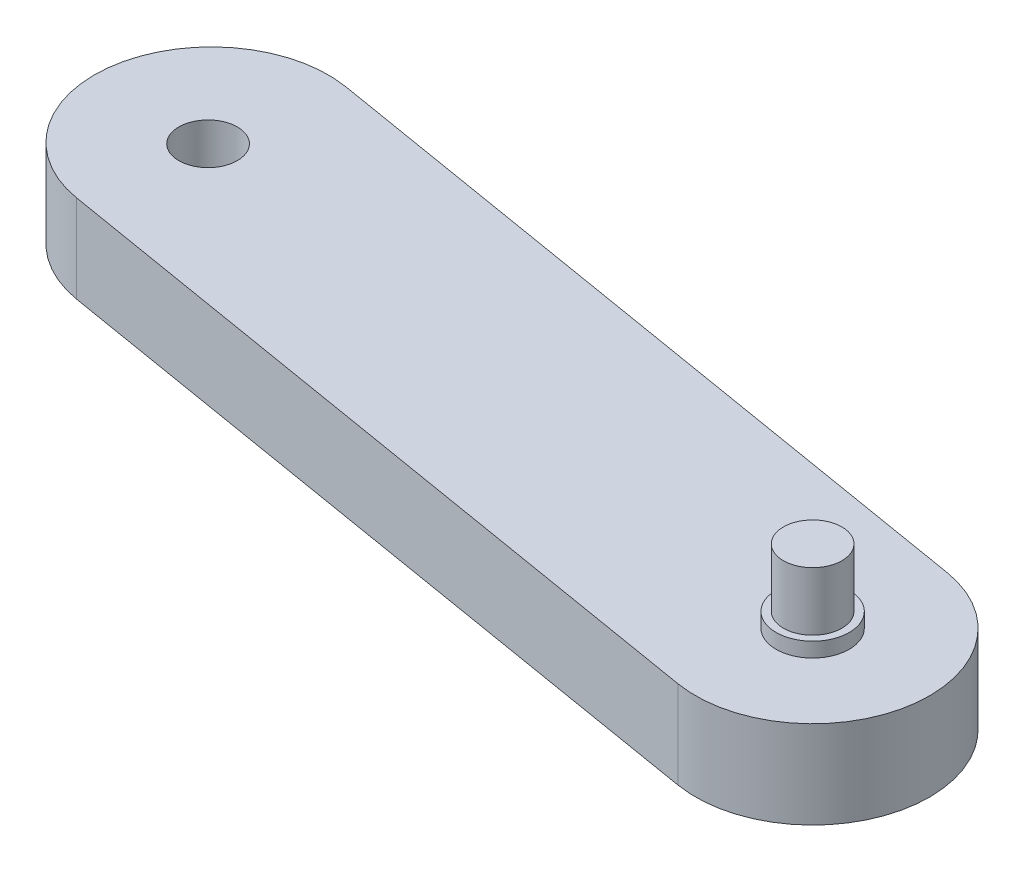
SolidWorks part; units mm, degrees
ref_plane "Piano frontale" through (0, 0, 0) normal (0, 0, 1) x (1, 0, 0)
ref_plane "Piano superiore" through (0, 0, 0) normal (0, 1, 0) x (1, 0, 0)
ref_plane "Piano destro" through (0, 0, 0) normal (1, 0, 0) x (0, 0, -1)
sketch "Sketch1" plane through (0, 0, 0) normal (0, 0, 1) x (1, 0, 0)
  line L0 (0, 8) -> (50, 8)
  line L1 (0, -8) -> (50, -8)
  arc A2 (50, 8) -> (50, -8) centre (50, 0) cw
  arc A3 (0, 8) -> (0, -8) centre (0, 0) ccw
extrude "Boss-Extrude1" add sketch "Sketch1" along normal blind 6 contours L0 A3 L1 A2
sketch "Sketch4" plane through (0, 0, 0) normal (0, 0, -1) x (-1, 0, 0)
  circle A0 centre (-50, 0) radius 2.5
extrude "Boss-Extrude3" add sketch "Sketch4" along normal blind 5
move or copy body "Body-Move/Copy1" bodies to move or copy 106 copy no rotation origin (0, 0, 11) rotation axis (-1, 0, 0) rotation angle 90
sketch "Sketch8" plane through (0, -16, 0) normal (0, -1, 0) x (1, 0, 0)
  circle A0 centre (50, 11) radius 2
  circle A1 centre (50, 11) radius 2.5
extrude "Cut-Extrude4" cut sketch "Sketch8" against normal blind 4
sketch "Sketch9" plane through (0, -11, 0) normal (0, -1, 0) x (1, 0, 0)
  circle A0 centre (0, 11) radius 2
move or copy body "Body-Move/Copy2" bodies to move or copy 112 copy no rotation origin (-0.8727, 0, 2.7305) rotation axis (0.9525, 0, 0.3044) rotation angle 180
move or copy body "Body-Move/Copy3" bodies to move or copy 115 copy no rotation origin (25, 0, 11) rotation axis (0, 1, 0) rotation angle 35
move or copy body "Body-Move/Copy4" bodies to move or copy 116 copy no rotation origin (0, 0, 11) rotation axis (1, 0, 0) rotation angle 180
extrude "Cut-Extrude5" cut sketch "Sketch9" against normal blind 10
move or copy body "Body-Move/Copy5" bodies to move or copy 118 copy no rotation origin (-0.7066, -10.5, 8.9764) rotation axis (0.9969, 0, 0.0785) rotation angle 180
